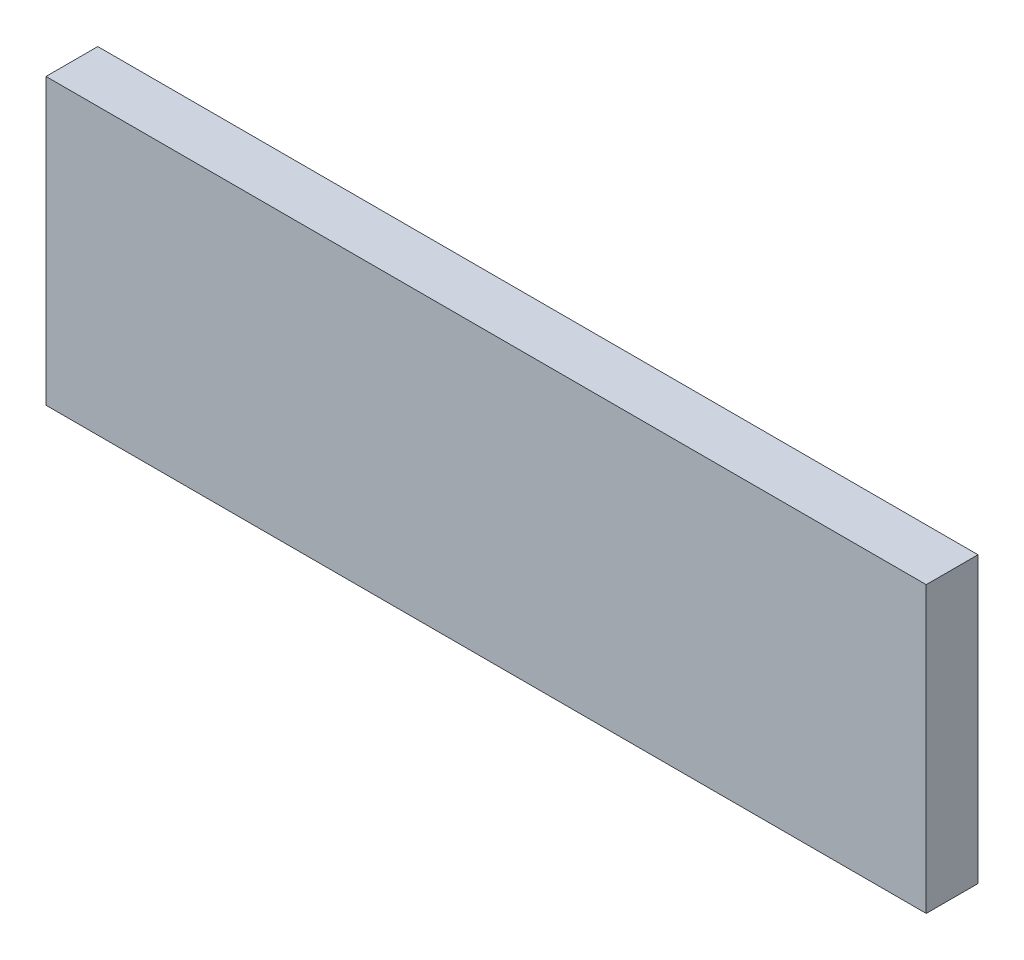
SolidWorks part; units mm, degrees
ref_plane "Front Plane" through (0, 0, 0) normal (0, 0, 1) x (1, 0, 0)
ref_plane "Top Plane" through (0, 0, 0) normal (0, 1, 0) x (1, 0, 0)
ref_plane "Right Plane" through (0, 0, 0) normal (1, 0, 0) x (0, 0, -1)
sketch "Sketch1" plane through (0, 0, 0) normal (0, 0, 1) x (1, 0, 0)
  line L1 (-85, -27.5) -> (85, -27.5)
  line L2 (-85, -27.5) -> (-85, 27.5)
  line L3 (-85, 27.5) -> (85, 27.5)
  line L4 (85, -27.5) -> (85, 27.5)
extrude "REFERENCE_ENVELOPE_NOT_MANUFACTURING" add sketch "Sketch1" along normal blind 10 from offset 0
